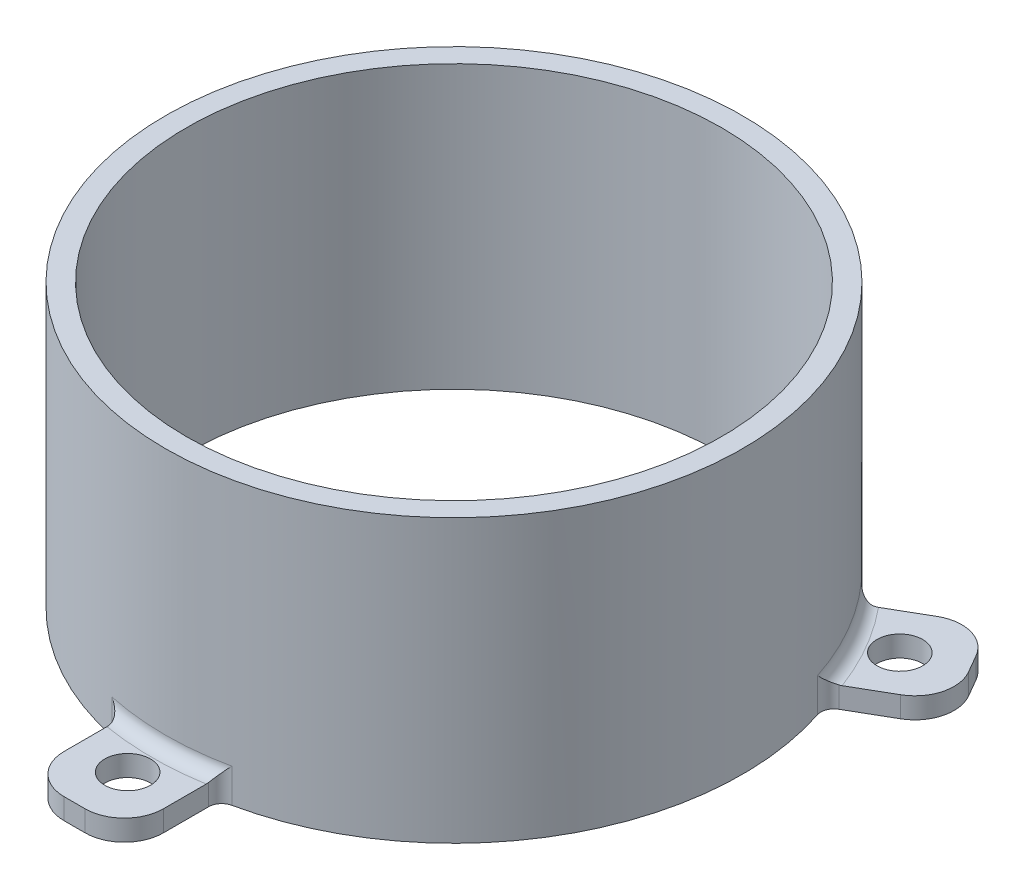
SolidWorks part; units mm, degrees
ref_plane "Front Plane" through (0, 0, 0) normal (0, 0, 1) x (1, 0, 0)
ref_plane "Top Plane" through (0, 0, 0) normal (0, 1, 0) x (1, 0, 0)
ref_plane "Right Plane" through (0, 0, 0) normal (1, 0, 0) x (0, 0, -1)
sketch "Sketch1" plane through (0, 0, 0) normal (0, 1, 0) x (1, 0, 0)
  circle A0 centre (0, 0) radius 20.5
  dimension "D1" = 41
extrude "Boss-Extrude2" add sketch "Sketch1" along normal blind 20
shell "Shell1" thickness 1.6
sketch "Sketch7" plane through (0, 0, 0) normal (0, 1, 0) x (1, 0, 0)
  circle A0 centre (0, 0) radius 20.5
extrude "Cut-Extrude1" cut sketch "Sketch7" against normal blind 10
sketch "Sketch8" plane through (0, 0, 0) normal (0, 1, 0) x (1, 0, 0)
  line L0 (-3.8039, -20.8629) -> (-3.8039, -26.0629)
  line L1 (-0.8039, -29.0629) -> (0.8039, -29.0629)
  line L2 (3.8039, -26.0629) -> (3.8039, -20.8629)
  line L3 (-16.1659, 13.7257) -> (-20.6692, 16.3257)
  line L4 (-24.7673, 15.2276) -> (-25.5712, 13.8353)
  line L5 (-24.4731, 9.7372) -> (-19.9698, 7.1372)
  line L6 (19.9698, 7.1372) -> (24.4731, 9.7372)
  line L7 (25.5712, 13.8353) -> (24.7673, 15.2276)
  line L8 (20.6692, 16.3257) -> (16.1659, 13.7257)
  line L9 (0, 0) -> (0, -25) construction
  arc A0 (0.8039, -29.0629) -> (3.8039, -26.0629) centre (0.8039, -26.0629) ccw
  arc A2 (-3.8039, -20.8629) -> (3.8039, -20.8629) centre (0, -4.1973) ccw
  arc A3 (-0.8039, -29.0629) -> (-3.8039, -26.0629) centre (-0.8039, -26.0629) cw
  arc A4 (-25.5712, 13.8353) -> (-24.4731, 9.7372) centre (-22.9731, 12.3353) ccw
  arc A5 (-16.1659, 13.7257) -> (-19.9698, 7.1372) centre (-3.635, 2.0987) ccw
  arc A6 (-24.7673, 15.2276) -> (-20.6692, 16.3257) centre (-22.1692, 13.7276) cw
  arc A7 (24.7673, 15.2276) -> (20.6692, 16.3257) centre (22.1692, 13.7276) ccw
  arc A8 (19.9698, 7.1372) -> (16.1659, 13.7257) centre (3.635, 2.0987) ccw
  arc A9 (25.5712, 13.8353) -> (24.4731, 9.7372) centre (22.9731, 12.3353) cw
  circle A10 centre (0, -25) radius 1.75
  circle A11 centre (-21.6506, 12.5) radius 1.75
  circle A12 centre (21.6506, 12.5) radius 1.75
  point P30 (0, 0)
  point P39 (0, 0)
  dimension "D1" = 3
  dimension "D3" = 3
  dimension "D2" = 3
extrude "Boss-Extrude3" add sketch "Sketch8" against normal blind 1.6
fillet "Fillet1" radius 1 9 edges at (-16.9516, -0.8, -14.1794) (-19.1392, 0, -11.05) (-20.7555, -0.8, -7.5908) (-3.8039, -0.8, 21.7702) (0, 0, 22.1) (3.8039, -0.8, 21.7702) (20.7555, -0.8, -7.5908) (19.1392, 0, -11.05) (16.9516, -0.8, -14.1794)
